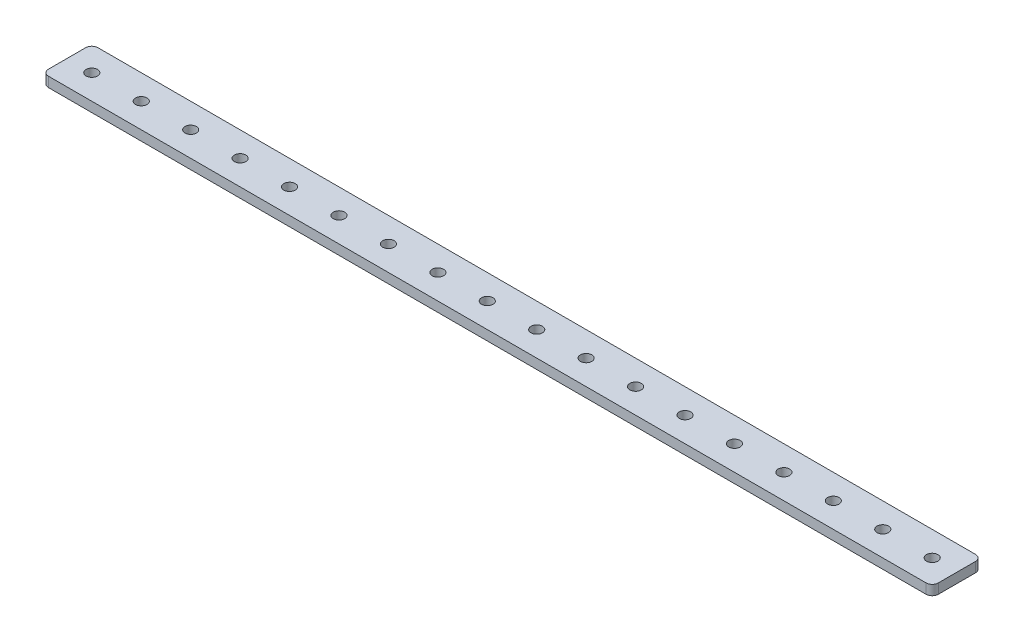
SolidWorks part; units mm, degrees
material "5052 Alloy"
ref_plane "Front Plane" through (0, 0, 0) normal (0, 0, 1) x (1, 0, 0)
ref_plane "Top Plane" through (0, 0, 0) normal (0, 1, 0) x (1, 0, 0)
ref_plane "Right Plane" through (0, 0, 0) normal (1, 0, 0) x (0, 0, -1)
sketch "Sketch1" plane through (0, 0, 0) normal (0, 1, 0) x (1, 0, 0)
  line L0 (144, 0) -> (-144, 0) construction
  line L1 (-144, -8) -> (144, -8)
  line L2 (-144, -8) -> (-144, 8)
  line L3 (-144, 8) -> (144, 8)
  line L4 (144, -8) -> (144, 8)
  dimension "D1" = 288
  dimension "D2" = 16
extrude "Extrude1" add sketch "Sketch1" along normal mid plane 3.2
sketch "Sketch2" plane through (0, 1.6, 0) normal (0, 1, 0) x (1, 0, 0)
  line L0 (-144, 8) -> (-144, -8) construction
  line L1 (-144, 0) -> (144, 0) construction
  line L3 (144, -8) -> (144, 8) construction
  circle A0 centre (-136, 0) radius 1.85
  dimension "D1" = 3.7
  dimension "D2" = 8
extrude "Cut-Extrude1" cut sketch "Sketch2" against normal up to next
pattern_linear "LPattern1" count 18 spacing 16 along (1, 0, 0) of "Cut-Extrude1"
fillet "Fillet1" radius 2 4 edges at (144, 0, 8) (-144, 0, 8) (-144, 0, -8) (144, 0, -8)
